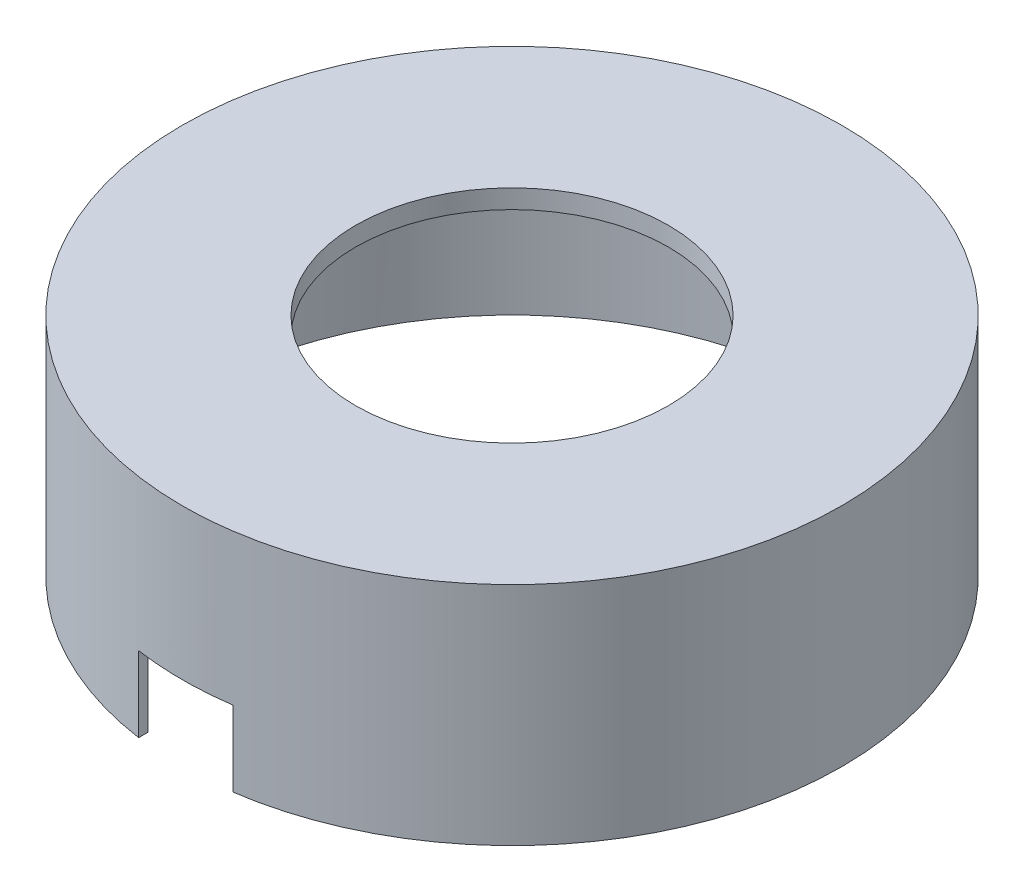
SolidWorks part; units mm, degrees
ref_plane "Front Plane" through (0, 0, 0) normal (0, 0, 1) x (1, 0, 0)
ref_plane "Top Plane" through (0, 0, 0) normal (0, 1, 0) x (1, 0, 0)
ref_plane "Right Plane" through (0, 0, 0) normal (1, 0, 0) x (0, 0, -1)
sketch "Sketch1" plane through (0, 0, 0) normal (0, 1, 0) x (1, 0, 0)
  circle A0 centre (0, 0) radius 87.5
  dimension "D1" = 175
extrude "Boss-Extrude1" add sketch "Sketch1" along normal blind 60 contours A0
sketch "Sketch2" plane through (0, 0, 0) normal (0, -1, 0) x (1, 0, 0)
  circle A0 centre (0, 0) radius 85
extrude "Cut-Extrude1" cut sketch "Sketch2" against normal blind 55
sketch "Sketch3" plane through (0, 55, 0) normal (0, -1, 0) x (1, 0, 0)
  circle A0 centre (0, 0) radius 41.5
  dimension "D1" = 83
extrude "Cut-Extrude2" cut sketch "Sketch3" against normal up to next
ref_plane "Plane2" through (0, 0, 87.5) normal (0, 0, 1) x (1, 0, 0)
sketch "Sketch4" plane through (0, 0, 87.5) normal (0, 0, 1) x (1, 0, 0)
  line L0 (0, -33) -> (0, 33) construction
  line L1 (-12.5, 20) -> (12.5, 20)
  line L2 (-12.5, 20) -> (-12.5, 0)
  line L3 (-12.5, 0) -> (12.5, 0)
  line L4 (12.5, 20) -> (12.5, 0)
  line L5 (-12.5, 20) -> (12.5, 0) construction
  line L6 (-12.5, 0) -> (12.5, 20) construction
  line L7 (96.25, 0) -> (-96.25, 0) construction
  point P0 (0, 10)
  dimension "D1" = 25
  dimension "D2" = 20
extrude "Cut-Extrude3" cut sketch "Sketch4" against normal up to next
ref_plane "Plane4" through (0, 0, -87.5) normal (0, 0, 1) x (1, 0, 0)
sketch "Sketch5" plane through (0, 0, -87.5) normal (0, 0, 1) x (1, 0, 0)
  line L0 (0, -33) -> (0, 33) construction
  line L1 (13.1, 46.5053) -> (6.9, 46.5053)
  line L2 (13.1, 46.5053) -> (13.1, 40.3053)
  line L3 (13.1, 40.3053) -> (6.9, 40.3053)
  line L4 (6.9, 46.5053) -> (6.9, 40.3053)
  line L5 (13.1, 46.5053) -> (6.9, 40.3053) construction
  line L6 (13.1, 40.3053) -> (6.9, 46.5053) construction
  line L7 (-6.9, 46.5053) -> (-13.1, 46.5053)
  line L8 (-6.9, 46.5053) -> (-6.9, 40.1117)
  line L9 (-6.9, 40.1117) -> (-13.1, 40.1117)
  line L10 (-13.1, 46.5053) -> (-13.1, 40.1117)
  line L11 (-6.9, 46.5053) -> (-13.1, 40.1117) construction
  line L12 (-6.9, 40.1117) -> (-13.1, 46.5053) construction
  point P0 (10, 43.4053)
  point P5 (-10, 43.3085)
  dimension "D1" = 6.2
  dimension "D2" = 6.2
  dimension "D3" = 6.2
  dimension "D4" = 10
  dimension "D5" = 10
extrude "Cut-Extrude5" cut sketch "Sketch5" along normal up to next
